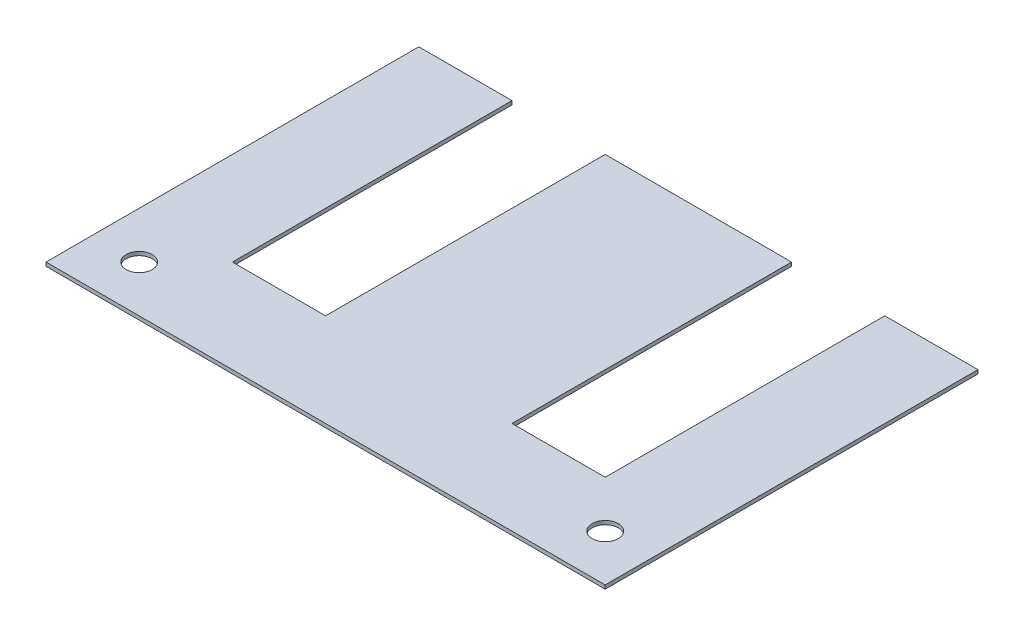
SolidWorks part; units mm, degrees
ref_plane "Alzado" through (0, 0, 0) normal (0, 0, 1) x (1, 0, 0)
ref_plane "Planta" through (0, 0, 0) normal (0, 1, 0) x (1, 0, 0)
ref_plane "Vista lateral" through (0, 0, 0) normal (1, 0, 0) x (0, 0, -1)
sketch "Croquis8" plane through (0, 0, 0) normal (0, 1, 0) x (1, 0, 0)
  line L0 (0, 0) -> (150, 0)
  line L1 (150, 0) -> (150, 100)
  line L2 (150, 100) -> (125, 100)
  line L3 (125, 100) -> (125, 25)
  line L4 (125, 25) -> (100, 25)
  line L5 (100, 25) -> (100, 100)
  line L6 (100, 100) -> (50, 100)
  line L7 (50, 100) -> (50, 25)
  line L8 (50, 25) -> (25, 25)
  line L9 (25, 25) -> (25, 100)
  line L10 (25, 100) -> (0, 100)
  line L11 (0, 100) -> (0, 0)
  circle A0 centre (12.5, 12.5) radius 3.5
  circle A1 centre (137.5, 12.5) radius 3.5
extrude "Saliente-Extruir5" add sketch "Croquis8" along normal blind 1
